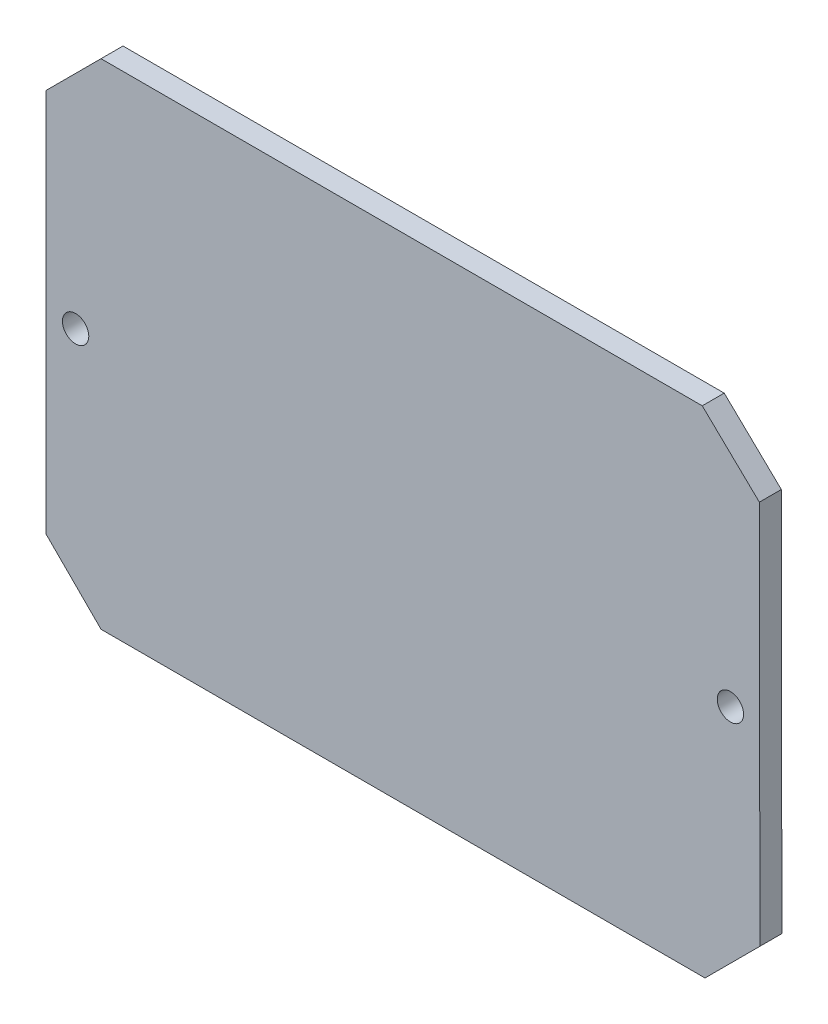
SolidWorks part; units mm, degrees
ref_plane "Front Plane" through (0, 0, 0) normal (0, 0, 1) x (1, 0, 0)
ref_plane "Top Plane" through (0, 0, 0) normal (0, 1, 0) x (1, 0, 0)
ref_plane "Right Plane" through (0, 0, 0) normal (1, 0, 0) x (0, 0, -1)
sketch "Sketch1" plane through (0, 0, 0) normal (0, 0, 1) x (1, 0, 0)
  line L0 (153.8307, 29.2759) -> (153.9883, -81.8522)
  line L1 (153.9883, -81.8522) -> (138.1133, -97.7272)
  line L2 (138.1133, -97.7272) -> (-36.5117, -97.7272)
  line L3 (-36.5117, -97.7272) -> (-52.3867, -81.8522)
  line L4 (-52.3867, -81.8522) -> (-52.3867, 29.2728)
  line L5 (-52.3867, 29.2728) -> (-36.5117, 45.1478)
  line L8 (-36.5117, 45.1478) -> (137.316, 45.1478)
  line L9 (137.316, 45.1478) -> (153.8307, 29.2759)
  circle A0 centre (145.4613, -26.141) radius 3.81
  circle A1 centre (-43.8614, -26.141) radius 3.81
  dimension "D1" = 7.62
  dimension "D2" = 7.62
extrude "Extrude1" add sketch "Sketch1" along normal blind 6.35
